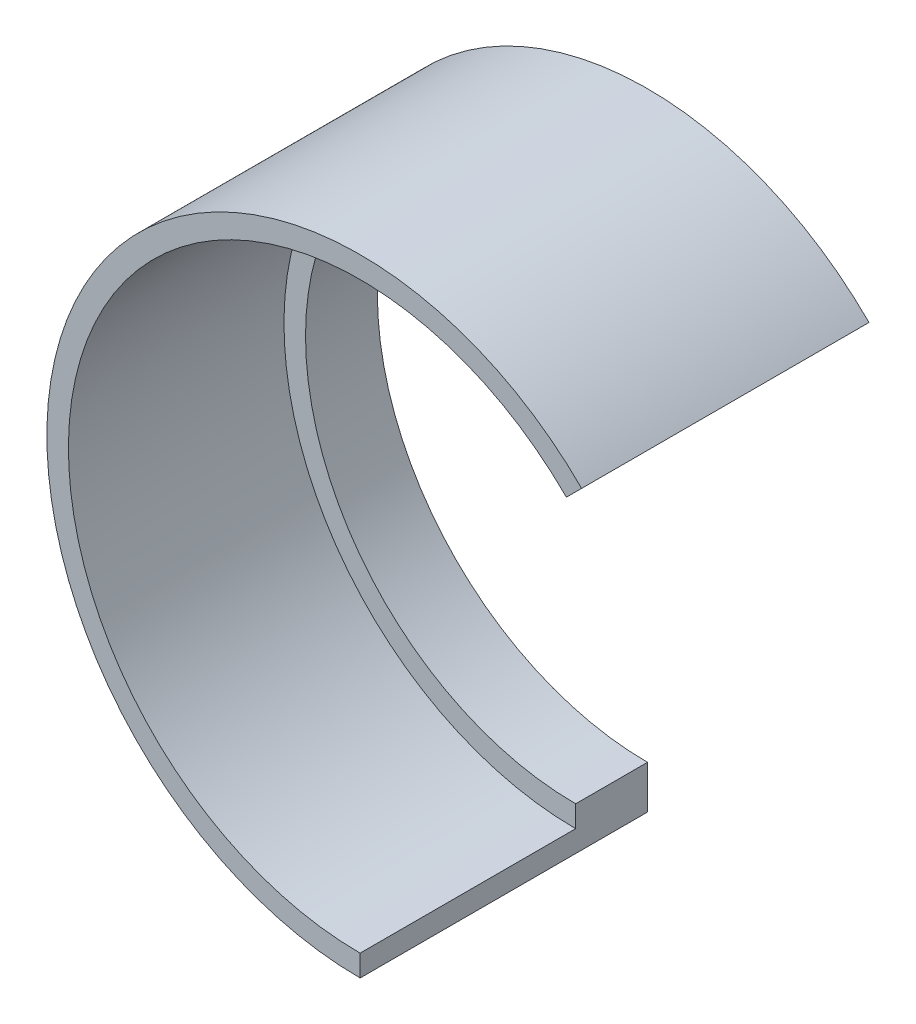
SolidWorks part; units mm, degrees
ref_plane "前视基准面" through (0, 0, 0) normal (0, 0, 1) x (1, 0, 0)
ref_plane "上视基准面" through (0, 0, 0) normal (0, 1, 0) x (1, 0, 0)
ref_plane "右视基准面" through (0, 0, 0) normal (1, 0, 0) x (0, 0, -1)
other "Configuration Table"
sketch "草图1" plane through (0, 0, 0) normal (0, 0, 1) x (1, 0, 0)
  line L0 (0, 0) -> (0, -40.6)
  line L1 (0, -40.6) -> (0, 0)
  line L2 (0, 0) -> (28.7085, 28.7085)
  circle A0 centre (0, 0) radius 37.6
  circle A1 centre (0, 0) radius 40.6
  dimension "D1" = 75.2
  dimension "D3" = 135
  dimension "D2" = 3
extrude "凸台-拉伸1" add sketch "草图1" along normal blind 10 contours L2 A1 L1 A0
sketch "草图2" plane through (0, 0, 10) normal (0, 0, 1) x (1, 0, 0)
  line L2 (26.5872, 26.5872) -> (30.8299, 30.8299)
  line L3 (30.8299, 30.8299) -> (0, 0)
  line L4 (0, 0) -> (0, -43.6)
  circle A2 centre (0, 0) radius 40.6
  circle A3 centre (0, 0) radius 43.6
  arc M2 (28.7085, 28.7085) -> (0, -40.6) centre (0, 0) ccw
  dimension "D1" = 3
extrude "凸台-拉伸2" add sketch "草图2" along normal blind 30 and the other way up to surface (10 mm away) contours L2 A3 L4 M2 other way up to face at (-11.1499, 4.6184, 0)
